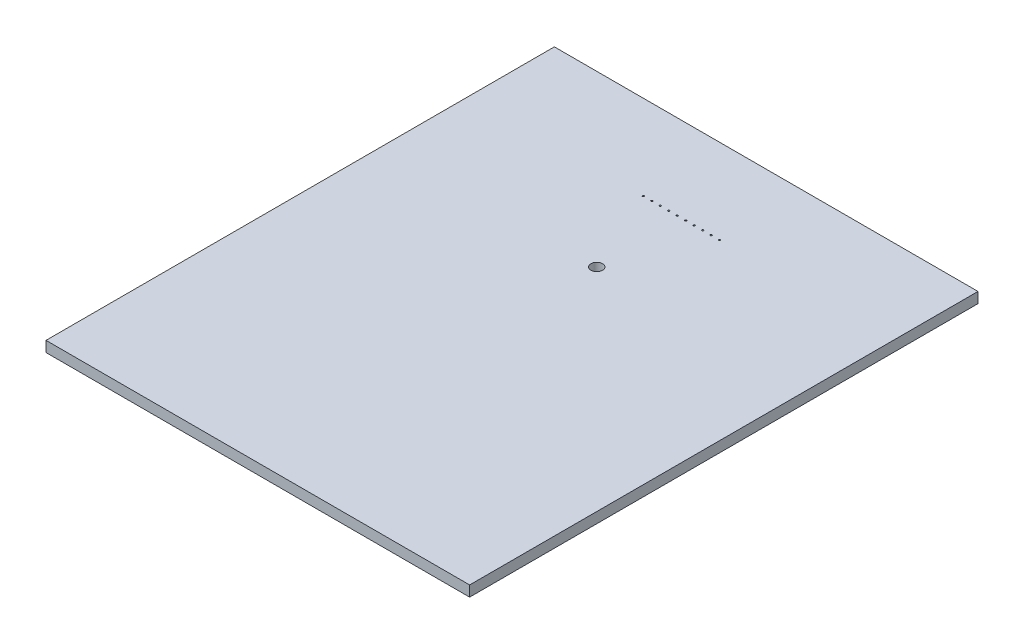
SolidWorks part; units mm, degrees
ref_plane "Front" through (0, 0, 0) normal (0, 0, 1) x (1, 0, 0)
ref_plane "Top" through (0, 0, 0) normal (0, 1, 0) x (1, 0, 0)
ref_plane "Right" through (0, 0, 0) normal (1, 0, 0) x (0, 0, -1)
sketch "Sketch1" plane through (0, 0, 0) normal (0, 1, 0) x (1, 0, 0)
  line L1 (0, 0) -> (127, 0)
  line L2 (0, 0) -> (0, 152.4)
  line L3 (0, 152.4) -> (127, 152.4)
  line L4 (127, 0) -> (127, 152.4)
  dimension "D1" = 152.4
  dimension "D2" = 127
extrude "Boss-Extrude1" add sketch "Sketch1" along normal blind 3.175
sketch "Sketch6" plane through (0, 3.175, 0) normal (0, 1, 0) x (1, 0, 0)
  line L0 (63.5, 0) -> (63.5, 152.4) construction
  line L1 (0, 0) -> (127, 0) construction
  line L2 (127, 152.4) -> (0, 152.4) construction
  line L3 (0, 76.2) -> (127, 76.2) construction
  line L4 (0, 152.4) -> (0, 0) construction
  line L5 (127, 0) -> (127, 152.4) construction
  point P12 (63.5, 101.6)
  point P13 (0, 0)
  dimension "D1" = 25.4
hole_wizard "#8-32 Tapped Hole2" positions "3DSketch1" profile "Sketch7" tap size "#8-32" standard "ANSI Inch" end condition through all
sketch3d "3DSketch1"
  point P0 (63.5, 3.175, -101.6)
sketch "Sketch7" plane through (63.5, 3.175, -101.6) normal (1, 0, 0) x (0, 0, 1)
  line L0 (0, 0) -> (0, 3.175)
  line L1 (0, 3.175) -> (1.7272, 3.175)
  line L2 (1.7272, 3.175) -> (1.7272, 0)
  line L5 (1.7272, 0) -> (0, 0)
  line L11 (0, -6.35) -> (0, 107.95) construction
  dimension "Thru Tap Drill Dia." = 3.4544
  dimension "Thru Tap Drill Depth" = 3.175
cosmetic thread "Hole Thread2" parameters "D2"=4.1656
sketch "Sketch8" plane through (0, 3.175, 0) normal (0, 1, 0) x (1, 0, 0)
  line L0 (0, 76.2) -> (127, 76.2) construction
  line L1 (63.5, 0) -> (63.5, 152.4) construction
  line L2 (52.07, 127) -> (54.61, 127) construction
  circle A0 centre (52.07, 127) radius 0.2463
  circle A1 centre (54.61, 127) radius 0.2463
  circle A2 centre (57.15, 127) radius 0.2463
  circle A3 centre (59.69, 127) radius 0.2463
  circle A4 centre (62.23, 127) radius 0.2463
  circle A5 centre (64.77, 127) radius 0.2463
  circle A6 centre (67.31, 127) radius 0.2463
  circle A7 centre (69.85, 127) radius 0.2463
  circle A8 centre (72.39, 127) radius 0.2463
  circle A9 centre (74.93, 127) radius 0.2463
  dimension "D1" = 0.4926
  dimension "D2" = 50.8
  dimension "D3" = 11.43
  dimension "D5" = 2.54
  dimension "D4" = 10
extrude "Cut-Extrude1" cut sketch "Sketch8" against normal through all
